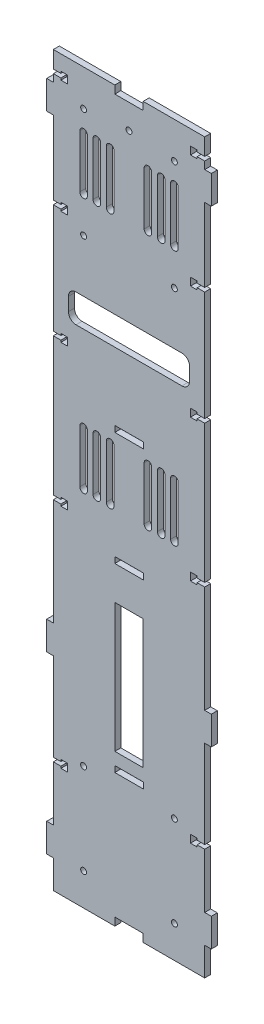
SolidWorks part; units mm, degrees
ref_plane "Front Plane" through (0, 0, 0) normal (0, 0, 1) x (1, 0, 0)
ref_plane "Top Plane" through (0, 0, 0) normal (0, 1, 0) x (1, 0, 0)
ref_plane "Right Plane" through (0, 0, 0) normal (1, 0, 0) x (0, 0, -1)
other "Center of Mass"
sketch "Sketch1" plane through (0, 0, 0) normal (0, 0, 1) x (1, 0, 0)
  line L1 (-50, 345) -> (30, 345)
  line L2 (-50, 345) -> (-50, -40)
  line L3 (-50, -40) -> (30, -40)
  line L4 (30, 345) -> (30, -40)
  dimension "D1" = 385
  dimension "D2" = 80
  dimension "D3" = 30
  dimension "D4" = 40
extrude "Boss-Extrude1" add sketch "Sketch1" against normal blind 3.175
sketch "Sketch2" plane through (0, 0, 0) normal (0, 0, 1) x (1, 0, 0)
  line L0 (-50, 345) -> (-50, -40) construction
  line L1 (-50, 330) -> (-53.5, 330)
  line L2 (-50, 330) -> (-50, 315)
  line L3 (-50, 315) -> (-53.5, 315)
  line L4 (-53.5, 330) -> (-53.5, 315)
  line L5 (30, 345) -> (-50, 345) construction
  line L7 (-50, 82.5) -> (-53.5, 82.5)
  line L8 (-50, 82.5) -> (-50, 67.5)
  line L9 (-50, 67.5) -> (-53.5, 67.5)
  line L10 (-53.5, 82.5) -> (-53.5, 67.5)
  line L11 (-50, -10) -> (-53.5, -10)
  line L12 (-50, -10) -> (-50, -25)
  line L13 (-50, -25) -> (-53.5, -25)
  line L14 (-53.5, -10) -> (-53.5, -25)
  dimension "D1" = 15
  dimension "D2" = 15
  dimension "D3" = 3.5
  dimension "D4" = 0
  dimension "D5" = 67.5
  dimension "D6" = 15
  dimension "D7" = 15
  dimension "D8" = 15
  dimension "D9" = 3.5
extrude "Boss-Extrude2" add sketch "Sketch2" against normal blind 3.175
sketch "Sketch6" plane through (0, 0, 0) normal (0, 0, 1) x (1, 0, 0)
  line L0 (-50, 336.05) -> (-46, 336.05)
  line L1 (-50, 345) -> (-50, 330) construction
  line L2 (-46, 336.05) -> (-46, 337.05)
  line L3 (-46, 337.05) -> (-42.5, 337.05)
  line L4 (-42.5, 337.05) -> (-42.5, 332.95)
  line L5 (-42.5, 332.95) -> (-46, 332.95)
  line L6 (-46, 332.95) -> (-46, 333.95)
  line L7 (-46, 333.95) -> (-50, 333.95)
  line L8 (-50, 333.95) -> (-50, 336.05)
  point P4 (-50, 335)
  dimension "D1" = 2.1
  dimension "D2" = 4.1
  dimension "D3" = 2.05
  dimension "D4" = 7.5
  dimension "D5" = 3.5
  dimension "D6" = 10
extrude "Cut-Extrude1" cut sketch "Sketch6" against normal blind 3.175
pattern_linear "LPattern1" count 2 spacing 60 along (0, -1, 0) of "Cut-Extrude1"
ref_plane "Plane1" through (-10, 0, 0) normal (-1, 0, 0) x (0, 0, 1)
mirror "Mirror1" about plane through (-10, 0, 0) normal (-1, 0, 0) of "Boss-Extrude2"
pattern_linear "LPattern2" count 2 spacing 120 along (0, -1, 0) of "Cut-Extrude1"
pattern_linear "LPattern3" count 2 spacing 195 along (0, -1, 0) of "Cut-Extrude1"
pattern_linear "LPattern6" count 2 spacing 315 along (0, -1, 0) of "Cut-Extrude1"
mirror "Mirror2" about plane through (-10, 0, 0) normal (-1, 0, 0) of "LPattern6", "Cut-Extrude1", "LPattern3", "LPattern2", "LPattern1"
sketch "Sketch7" plane through (0, 0, 0) normal (0, 0, 1) x (1, 0, 0)
  line L0 (30, 345) -> (-50, 345) construction
  line L1 (-17.5, 345) -> (-2.5, 345)
  line L2 (-17.5, 345) -> (-17.5, 340.825)
  line L3 (-17.5, 340.825) -> (-2.5, 340.825)
  line L4 (-2.5, 345) -> (-2.5, 340.825)
  line L5 (-50, -40) -> (30, -40) construction
  line L6 (-17.5, -40) -> (-2.5, -40)
  line L7 (-17.5, -40) -> (-17.5, -35.825)
  line L8 (-17.5, -35.825) -> (-2.5, -35.825)
  line L9 (-2.5, -40) -> (-2.5, -35.825)
  line L10 (-10, 1.7462) -> (-10, -1.7463) construction
  point P6 (-10, 345)
  point P7 (-10, -35.825)
  dimension "D1" = 15
  dimension "D2" = 4.175
  dimension "D4" = 4.175
  dimension "D5" = 15
extrude "Cut-Extrude2" cut sketch "Sketch7" against normal blind 10
sketch "Sketch8" plane through (0, 0, 0) normal (0, 0, 1) x (1, 0, 0)
  line L0 (1.7463, 0) -> (-1.7463, 0) construction
  line L1 (-17.5, 38.175) -> (-2.5, 38.175)
  line L2 (-17.5, 38.175) -> (-17.5, 35)
  line L3 (-17.5, 35) -> (-2.5, 35)
  line L4 (-2.5, 38.175) -> (-2.5, 35)
  line L5 (-2.5, -35.825) -> (-17.5, -35.825) construction
  point P6 (-10, 38.175)
  point P9 (-10, -35.825)
  dimension "D1" = 15
  dimension "D2" = 3.175
  dimension "D3" = 35
  dimension "D4" = 0
extrude "Cut-Extrude3" cut sketch "Sketch8" against normal blind 10
sketch "Sketch9" plane through (0, 0, 0) normal (0, 0, 1) x (1, 0, 0)
  line L0 (-17.5, 38.175) -> (-17.5, 35) construction
  line L1 (-17.5, 129.175) -> (-2.4, 129.175)
  line L2 (-17.5, 129.175) -> (-17.5, 125.975)
  line L3 (-17.5, 125.975) -> (-2.4, 125.975)
  line L4 (-2.4, 129.175) -> (-2.4, 125.975)
  line L6 (-2.5, 38.175) -> (-17.5, 38.175) construction
  dimension "D1" = 3.2
  dimension "D2" = 15.1
  dimension "D3" = 0
  dimension "D4" = 91
extrude "Cut-Extrude4" cut sketch "Sketch9" against normal through all
sketch "Sketch10" plane through (0, 0, 0) normal (0, 0, 1) x (1, 0, 0)
  line L0 (-17.5, 35) -> (-2.5, 35) construction
  line L1 (-34, 25) -> (14, 25) construction
  line L2 (14, 25) -> (14, -23) construction
  line L3 (14, -23) -> (-34, -23) construction
  line L4 (-34, -23) -> (-34, 25) construction
  line L7 (-10, 1.7462) -> (-10, -1.7463) construction
  circle A0 centre (-34, 25) radius 1.55
  circle A1 centre (-34, -23) radius 1.55
  circle A2 centre (14, 25) radius 1.55
  circle A3 centre (14, -23) radius 1.55
  point P11 (-10, 25)
  dimension "D1" = 3.1
  dimension "D2" = 10
  dimension "D4" = 48
  dimension "D5" = 3.1
  dimension "D7" = 3.1
  dimension "D11" = 3.1
  dimension "D9" = 48
extrude "Cut-Extrude5" cut sketch "Sketch10" against normal blind 10
sketch "Sketch11" plane through (0, 0, 0) normal (0, 0, 1) x (1, 0, 0)
  line L0 (-17.5, 340.825) -> (-2.5, 340.825) construction
  line L1 (14, 325.825) -> (14, 267.825) construction
  line L2 (14, 267.825) -> (-34, 267.825) construction
  line L3 (-34, 267.825) -> (-34, 325.825) construction
  line L4 (-34, 325.825) -> (14, 325.825) construction
  line L5 (-10, 1.7462) -> (-10, -1.7463) construction
  circle A0 centre (-34, 325.825) radius 1.55
  circle A1 centre (-34, 267.825) radius 1.55
  circle A2 centre (14, 325.825) radius 1.55
  circle A3 centre (14, 267.825) radius 1.55
  point P11 (-10, 325.825)
  dimension "D1" = 3.1
  dimension "D3" = 15
  dimension "D4" = 3.1
  dimension "D5" = 3.1
  dimension "D6" = 3.1
  dimension "D7" = 58
  dimension "D11" = 58
  dimension "D10" = 48
extrude "Cut-Extrude6" cut sketch "Sketch11" against normal through all
sketch "Sketch12" plane through (0, 0, 0) normal (0, 0, 1) x (1, 0, 0)
  line L0 (-2, 286.825) -> (-2, 314.825)
  line L1 (2, 314.825) -> (2, 286.825)
  line L2 (-17.5, 340.825) -> (-2.5, 340.825) construction
  arc A0 (-2, 314.825) -> (2, 314.825) centre (0, 314.825) cw
  arc A1 (-2, 286.825) -> (2, 286.825) centre (0, 286.825) ccw
  dimension "D1" = 2
  dimension "D2" = 28
  dimension "D3" = 0
  dimension "D4" = 26
extrude "Cut-Extrude7" cut sketch "Sketch12" against normal blind 10
pattern_linear "LPattern4" count 3 spacing 7 along (1, 0, 0) of "Cut-Extrude7"
mirror "Mirror4" about plane through (-10, 0, 0) normal (-1, 0, 0) of "LPattern4", "Cut-Extrude7"
sketch "Sketch14" plane through (0, 0, 0) normal (0, 0, 1) x (1, 0, 0)
  line L0 (-17.5, 340.825) -> (-2.5, 340.825) construction
  line L1 (-10, 1.7462) -> (-10, -1.7463) construction
  circle A0 centre (-10, 327.825) radius 1.55
  dimension "D1" = 3.1
  dimension "D2" = 13
extrude "Cut-Extrude9" cut sketch "Sketch14" against normal through all
pattern_linear "LPattern5" count 2 spacing 135 along (0, -1, 0) of "LPattern4", "Mirror4", "Cut-Extrude7"
sketch "Sketch15" plane through (0, 0, 0) normal (0, 0, 1) x (1, 0, 0)
  line L0 (-10, 1.7462) -> (-10, -1.7463) construction
  line L1 (-38, 240) -> (18, 240)
  line L2 (-42, 236) -> (-42, 229)
  line L3 (-38, 225) -> (18, 225)
  line L4 (22, 236) -> (22, 229)
  line L5 (-42, 240) -> (22, 225) construction
  line L6 (-42, 225) -> (22, 240) construction
  line L7 (-50, 273.95) -> (-50, 216.05) construction
  line L8 (30, 345) -> (-2.5, 345) construction
  arc A0 (18, 240) -> (22, 236) centre (18, 236) cw
  arc A1 (22, 229) -> (18, 225) centre (18, 229) cw
  arc A2 (-38, 225) -> (-42, 229) centre (-38, 229) cw
  arc A3 (-42, 236) -> (-38, 240) centre (-38, 236) cw
  point P0 (-10, 232.5)
  dimension "D4" = 4
  dimension "D1" = 15
  dimension "D2" = 8
  dimension "D3" = 105
extrude "Cut-Extrude10" cut sketch "Sketch15" against normal through all
pattern_linear "LPattern7" count 2 spacing 60 along (0, 1, 0) of "Cut-Extrude4"
sketch "Sketch17" plane through (0, 0, 0) normal (0, 0, 1) x (1, 0, 0)
  line L0 (-2.5, 35) -> (-2.5, 38.175) construction
  line L1 (-17.5, 38.175) -> (-2.5, 38.175)
  line L2 (-17.5, 38.175) -> (-17.5, 108.175)
  line L3 (-17.5, 108.175) -> (-2.5, 108.175)
  line L4 (-2.5, 38.175) -> (-2.5, 108.175)
  dimension "D1" = 70
extrude "Cut-Extrude11" cut sketch "Sketch17" against normal through all both and the other way through all
sketch "Sketch18" plane through (0, 0, 0) normal (0, 0, 1) x (1, 0, 0)
  line L0 (-2.5, 35) -> (-2.5, 108.175) construction
  line L1 (-17.5, 35) -> (-2.5, 35)
  line L2 (-17.5, 35) -> (-17.5, 40)
  line L3 (-17.5, 40) -> (-2.5, 40)
  line L4 (-2.5, 35) -> (-2.5, 40)
  dimension "D1" = 5
extrude "Boss-Extrude3" add sketch "Sketch18" against normal up to surface (3.175 mm away) up to face at (-9.95, 187.575, -3.175)
sketch "Sketch19" plane through (0, 0, 0) normal (0, 0, 1) x (1, 0, 0)
  line L0 (-17.5, 108.175) -> (-17.5, 40) construction
  line L1 (-17.5, 33.5) -> (-2.4, 33.5)
  line L2 (-17.5, 33.5) -> (-17.5, 30.3)
  line L3 (-17.5, 30.3) -> (-2.4, 30.3)
  line L4 (-2.4, 33.5) -> (-2.4, 30.3)
  line L5 (-2.5, 40) -> (-17.5, 40) construction
  dimension "D1" = 3.2
  dimension "D2" = 15.1
  dimension "D3" = 6.5
extrude "Cut-Extrude12" cut sketch "Sketch19" against normal through all
